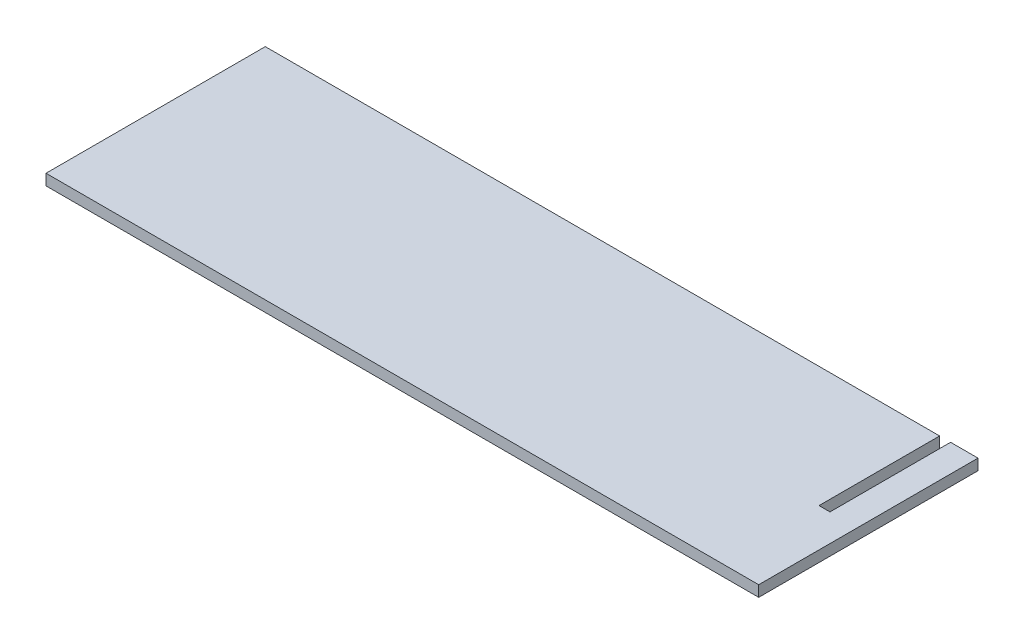
SolidWorks part; units mm, degrees
ref_plane "Front Plane" through (0, 0, 0) normal (0, 0, 1) x (1, 0, 0)
ref_plane "Top Plane" through (0, 0, 0) normal (0, 1, 0) x (1, 0, 0)
ref_plane "Right Plane" through (0, 0, 0) normal (1, 0, 0) x (0, 0, -1)
sketch "Sketch1" plane through (0, 0, 0) normal (0, 1, 0) x (1, 0, 0)
  line L0 (60, 20) -> (65, 20)
  line L1 (-65, 20) -> (58, 20)
  line L2 (-65, 20) -> (-65, -20)
  line L3 (-65, -20) -> (65, -20)
  line L4 (65, 20) -> (65, -20)
  line L5 (-65, 20) -> (65, -20) construction
  line L6 (-65, -20) -> (65, 20) construction
  line L8 (58, 20) -> (58, -2)
  line L9 (58, -2) -> (60, -2)
  line L10 (60, 20) -> (60, -2)
  point P0 (0, 0)
  dimension "D1" = 130
  dimension "D2" = 40
  dimension "D3" = 2
  dimension "D4" = 22
  dimension "D5" = 5
extrude "Boss-Extrude1" add sketch "Sketch1" along normal mid plane 2
